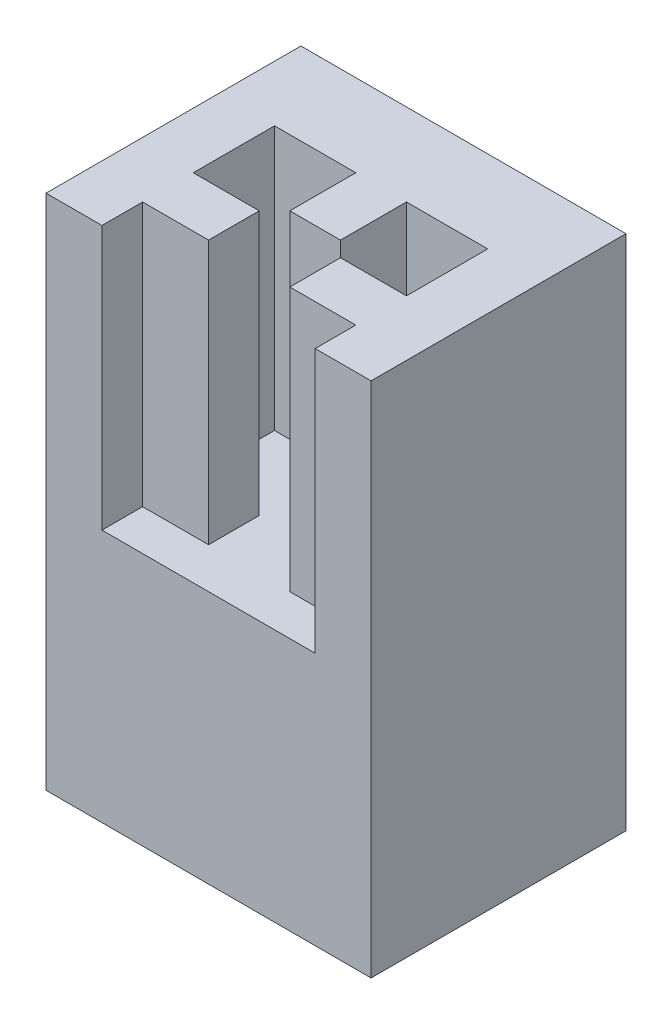
SolidWorks part; units mm, degrees
ref_plane "Plan de face" through (0, 0, 0) normal (0, 0, 1) x (1, 0, 0)
ref_plane "Plan de dessus" through (0, 0, 0) normal (0, 1, 0) x (1, 0, 0)
ref_plane "Plan de droite" through (0, 0, 0) normal (1, 0, 0) x (0, 0, -1)
sketch "Esquisse1" plane through (0, 0, 0) normal (0, 1, 0) x (1, 0, 0)
  line L1 (-39.5605, 3.8269) -> (-8.7605, 3.8269)
  line L2 (-39.5605, 3.8269) -> (-39.5605, -20.3231)
  line L3 (-39.5605, -20.3231) -> (-8.7605, -20.3231)
  line L4 (-8.7605, 3.8269) -> (-8.7605, -20.3231)
  line L5 (-39.5605, 3.8269) -> (-8.7605, -20.3231) construction
  line L6 (-39.5605, -20.3231) -> (-8.7605, 3.8269) construction
  point P0 (-24.1605, -8.2481)
  dimension "D1" = 30.8
  dimension "D2" = 24.15
extrude "Boss.-Extru.1" add sketch "Esquisse1" along normal blind 49
sketch "Esquisse2" plane through (0, 49, 0) normal (0, 1, 0) x (1, 0, 0)
  line L0 (-34.2605, -20.3231) -> (-34.2605, -16.4731)
  line L1 (-39.5605, -20.3231) -> (-8.7605, -20.3231) construction
  line L2 (-34.2605, -16.4731) -> (-28.0105, -16.4731)
  line L3 (-28.0105, -16.4731) -> (-28.0105, -11.6731)
  line L4 (-28.0105, -11.6731) -> (-34.2605, -11.6731)
  line L5 (-34.2605, -11.6731) -> (-34.2605, -3.9731)
  line L6 (-34.2605, -3.9731) -> (-26.5605, -3.9731)
  line L7 (-26.5605, -3.9731) -> (-26.5605, -10.2231)
  line L8 (-26.5605, -10.2231) -> (-21.7605, -10.2231)
  line L9 (-21.7605, -10.2231) -> (-21.7605, -3.9731)
  line L10 (-21.7605, -3.9731) -> (-14.0605, -3.9731)
  line L11 (-14.0605, -3.9731) -> (-14.0605, -11.6731)
  line L12 (-14.0605, -11.6731) -> (-20.3105, -11.6731)
  line L13 (-20.3105, -11.6731) -> (-20.3105, -16.4731)
  line L14 (-20.3105, -16.4731) -> (-14.0605, -16.4731)
  line L15 (-14.0605, -16.4731) -> (-14.0605, -20.3231)
  line L16 (-39.5605, 3.8269) -> (-39.5605, -20.3231) construction
  dimension "D1" = 3.85
  dimension "D2" = 6.25
  dimension "D3" = 4.8
  dimension "D4" = 6.25
  dimension "D5" = 7.7
  dimension "D6" = 7.7
  dimension "D7" = 6.25
  dimension "D8" = 4.8
  dimension "D9" = 6.25
  dimension "D10" = 7.7
  dimension "D11" = 7.7
  dimension "D12" = 6.25
  dimension "D13" = 4.8
  dimension "D14" = 6.25
  dimension "D15" = 5.3
sketch "Esquisse3" plane through (0, 0, 0) normal (0, -1, 0) x (-1, 0, 0)
  line L0 (39.5605, 3.8269) -> (39.5605, -20.3231) construction
  line L3 (39.5605, -20.3231) -> (8.7605, -20.3231) construction
  circle A0 centre (24.1605, -8.3231) radius 2.75
  dimension "D1" = 5.5
  dimension "D2" = 15.4
  dimension "D3" = 12
extrude "Enlèv. mat.-Extru.3" cut sketch "Esquisse3" against normal blind 22
extrude "Enlèv. mat.-Extru.4" cut sketch "Esquisse2" against normal blind 25 and the other way through all flip side to cut
